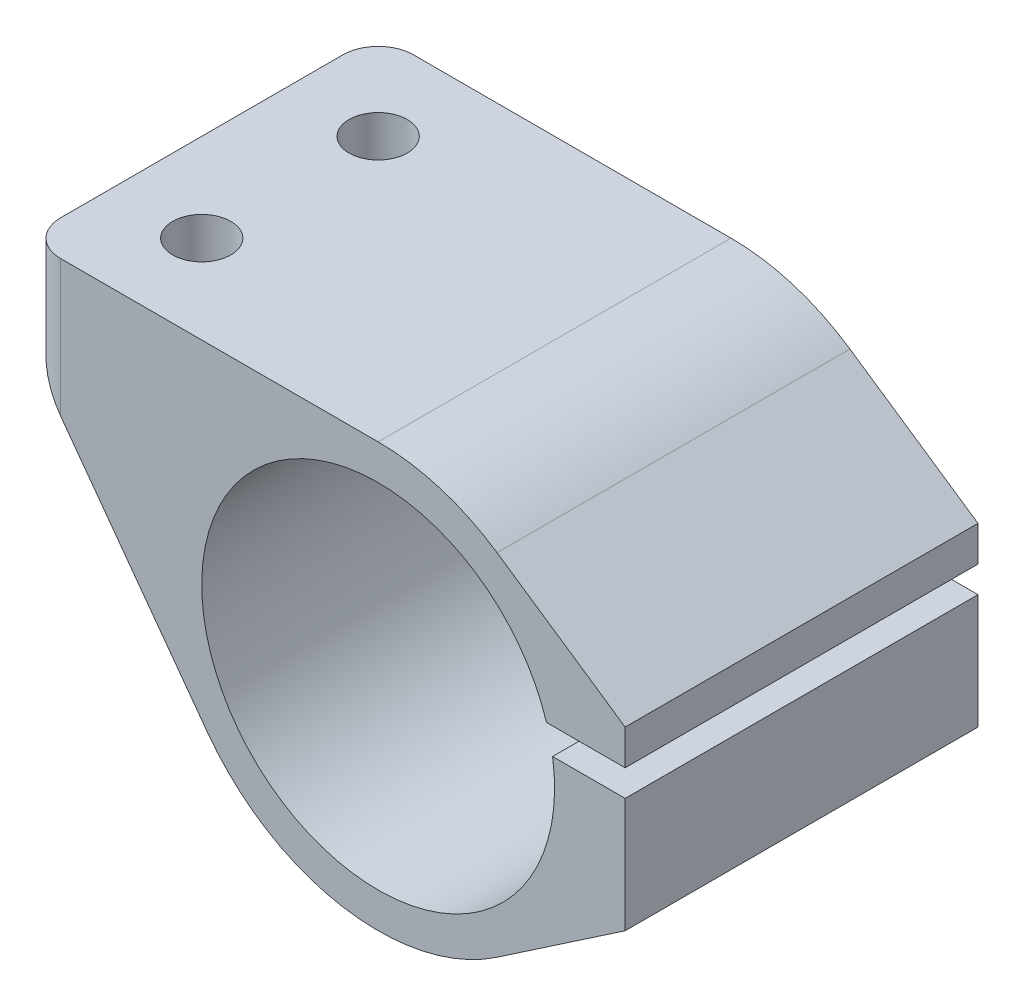
SolidWorks part; units mm, degrees
ref_plane "Plan de face" through (0, 0, 0) normal (0, 0, 1) x (1, 0, 0)
ref_plane "Plan de dessus" through (0, 0, 0) normal (0, 1, 0) x (1, 0, 0)
ref_plane "Plan de droite" through (0, 0, 0) normal (1, 0, 0) x (0, 0, -1)
sketch "Esquisse1" plane through (0, 0, 0) normal (0, 0, 1) x (1, 0, 0)
  point P0 (0, 0)
  line B0 (6.7398, -9.9285) -> (14, -5)
  line B1 (14, -5) -> (14, 1.5)
  line B2 (14, 1.5) -> (9.8869, 1.5)
  line B3 (9.5394, 3) -> (14, 3)
  line B4 (14, 3) -> (14, 5)
  line B5 (14, 5) -> (6.7398, 9.9285)
  arc B6 (6.7398, 9.9285) -> (6.7398, -9.9285) centre (0, 0) ccw
  arc B7 (9.5394, 3) -> (9.8869, 1.5) centre (0, 0) ccw
sketch_block_instance "Bloc1-1"
sketch_block "Bloc1"
extrude "Boss.-Extru.1" add sketch "Esquisse1" along normal blind 20
sketch "Esquisse2" plane through (0, 0, 20) normal (0, 0, 1) x (1, 0, 0)
  line L0 (0, 12) -> (-20, 12)
  line L1 (-20, 12) -> (-20, 7)
  line L2 (-20, 7) -> (-9.6815, -7.09)
  arc A0 (6.7398, 9.9285) -> (6.7398, -9.9285) centre (0, 0) ccw construction
  circle A1 centre (0, 0) radius 12 construction
  arc A2 (-9.6815, -7.09) -> (0, 12) centre (0, 0) cw
  dimension "D1" = 5
  dimension "D2" = 20
extrude "Boss.-Extru.2" add sketch "Esquisse2" against normal up to vertex (20 mm away)
sketch "Esquisse3" plane through (0, 12, 0) normal (0, 1, 0) x (1, 0, 0)
  line L0 (-15, 0) -> (-15, -20) construction
  line L1 (0, 0) -> (-20, 0) construction
  line L2 (0, -20) -> (-20, -20) construction
  line L3 (-20, -10) -> (14, -10) construction
  line L4 (-20, 0) -> (-20, -20) construction
  line L5 (14, -20) -> (14, 0) construction
  circle A0 centre (-15, -5) radius 1.65
  circle A1 centre (-15, -15) radius 1.65
  dimension "D2" = 3.3
  dimension "D1" = 10
  dimension "D3" = 5
extrude "Enlèv. mat.-Extru.1" cut sketch "Esquisse3" against normal through all
fillet "Congé1" radius 2 2 edges at (-20, 9.5, 20) (-20, 9.5, 0)
